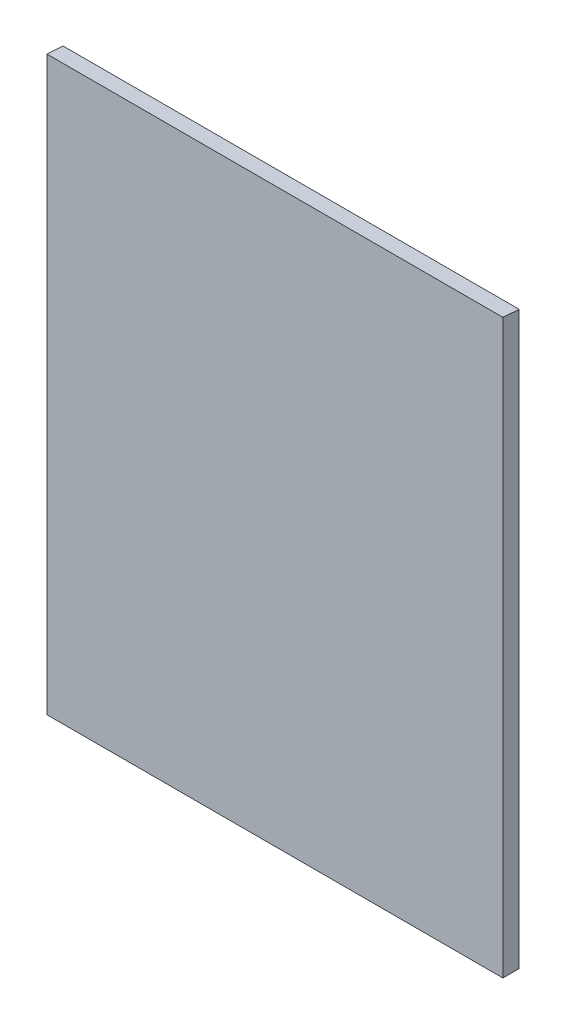
SolidWorks part; units mm, degrees
ref_plane "Front Plane" through (0, 0, 0) normal (0, 0, 1) x (1, 0, 0)
ref_plane "Top Plane" through (0, 0, 0) normal (0, 1, 0) x (1, 0, 0)
ref_plane "Right Plane" through (0, 0, 0) normal (1, 0, 0) x (0, 0, -1)
sketch "Sketch1" plane through (0, 0, 0) normal (0, 0, 1) x (1, 0, 0)
  line L1 (-266.573, 2683.51) -> (266.573, 2683.51)
  line L2 (-266.573, 2683.51) -> (-266.573, 3352.3095)
  line L3 (-266.573, 3352.3095) -> (266.573, 3352.3095)
  line L4 (266.573, 2683.51) -> (266.573, 3352.3095)
  dimension "D1" = 668.7995
extrude "Boss-Extrude1" add sketch "Sketch1" against normal blind 19.05
sketch "Sketch2" plane through (-266.573, 0, 0) normal (-1, 0, 0) x (0, 0, 1)
  line L4 (0, 3352.3095) -> (-1.4255, 3371.3061)
  line L5 (-1.4255, 3371.3061) -> (-106.8941, 3363.3918)
  line L6 (-106.8941, 3363.3918) -> (-114.8538, 3343.691)
  line L7 (-114.8538, 3343.691) -> (0, 3352.3095)
  line L8 (0, 3352.3095) -> (-1.4255, 3371.3061)
  line L9 (-1.4255, 3371.3061) -> (-106.8941, 3363.3918)
  line L10 (-106.8941, 3363.3918) -> (-114.8538, 3343.691)
  line L11 (-114.8538, 3343.691) -> (0, 3352.3095)
  dimension "D1" = 0
extrude "Cut-Extrude1" cut sketch "Sketch2" against normal through all
